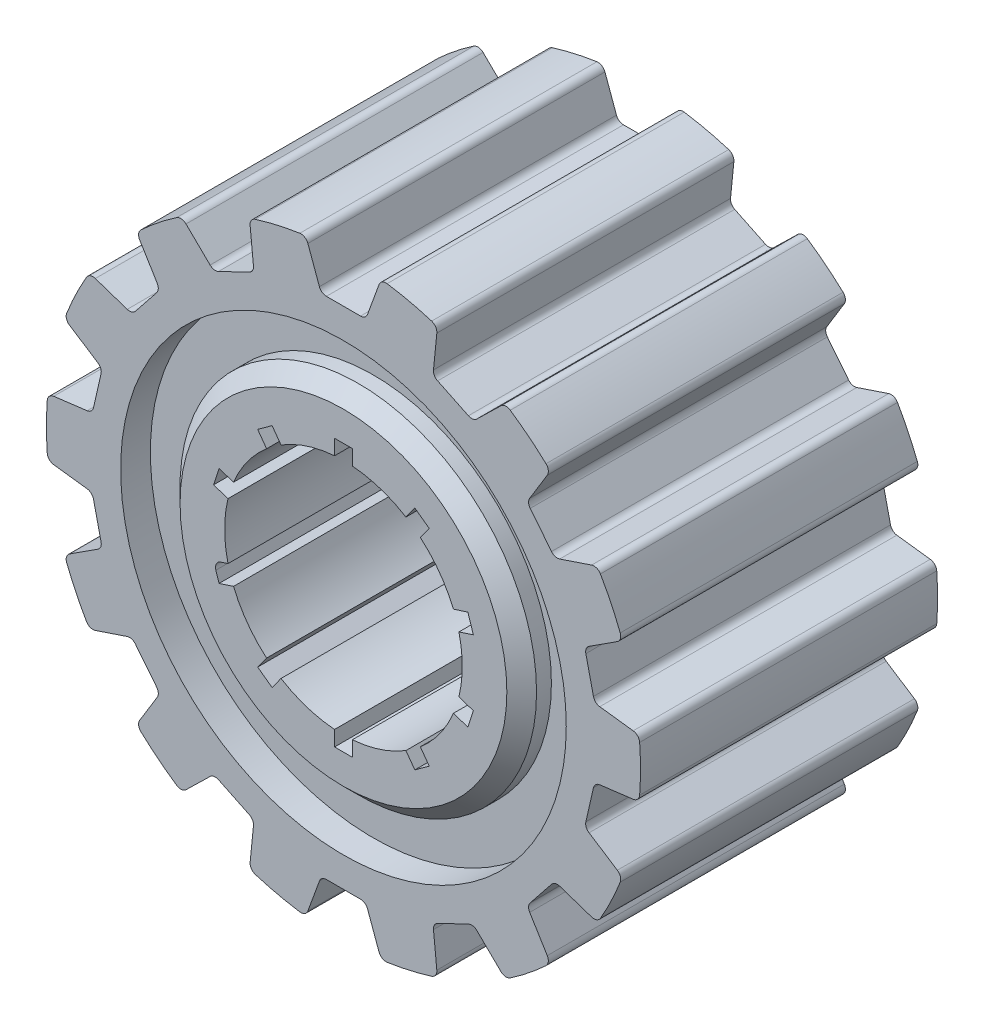
SolidWorks part; units mm, degrees
ref_plane "Front Plane" through (0, 0, 0) normal (0, 0, 1) x (1, 0, 0)
ref_plane "Top Plane" through (0, 0, 0) normal (0, 1, 0) x (1, 0, 0)
ref_plane "Right Plane" through (0, 0, 0) normal (1, 0, 0) x (0, 0, -1)
sketch "Sketch1" plane through (0, 0, 0) normal (0, 0, 1) x (1, 0, 0)
  line L0 (0, 0) -> (0, 1.4505) construction
  line L1 (0, 2.9752) -> (0, 4) construction
  line L2 (-0.3, 1.4505) -> (0.3, 1.4505)
  line L3 (-0.3, 3.9887) -> (-0.3, 4.5)
  line L4 (-0.3, 4.5) -> (0.3, 4.5)
  line L5 (0.3, 3.9887) -> (0.3, 4.5)
  line L6 (2.1018, 3.4033) -> (2.4023, 3.8169)
  line L7 (2.4023, 3.8169) -> (2.8877, 3.4642)
  line L8 (0, 4.5) -> (0, 6.1067) construction
  line L9 (2.5872, 3.0506) -> (2.8877, 3.4642)
  line L10 (3.7008, 1.5179) -> (4.187, 1.6759)
  line L11 (4.187, 1.6759) -> (4.3725, 1.1053)
  line L12 (3.8862, 0.9473) -> (4.3725, 1.1053)
  line L13 (3.8862, -0.9473) -> (4.3725, -1.1053)
  line L14 (4.3725, -1.1053) -> (4.187, -1.6759)
  line L15 (3.7008, -1.5179) -> (4.187, -1.6759)
  line L16 (2.5872, -3.0506) -> (2.8877, -3.4642)
  line L17 (2.8877, -3.4642) -> (2.4023, -3.8169)
  line L18 (2.1018, -3.4033) -> (2.4023, -3.8169)
  line L19 (0.3, -3.9887) -> (0.3, -4.5)
  line L20 (0.3, -4.5) -> (-0.3, -4.5)
  line L21 (-0.3, -3.9887) -> (-0.3, -4.5)
  line L22 (-2.1018, -3.4033) -> (-2.4023, -3.8169)
  line L23 (-2.4023, -3.8169) -> (-2.8877, -3.4642)
  line L24 (-2.5872, -3.0506) -> (-2.8877, -3.4642)
  line L25 (-3.7008, -1.5179) -> (-4.187, -1.6759)
  line L26 (-4.187, -1.6759) -> (-4.3725, -1.1053)
  line L27 (-3.8862, -0.9473) -> (-4.3725, -1.1053)
  line L28 (-3.8862, 0.9473) -> (-4.3725, 1.1053)
  line L29 (-4.3725, 1.1053) -> (-4.187, 1.6759)
  line L30 (-3.7008, 1.5179) -> (-4.187, 1.6759)
  line L31 (-2.5872, 3.0506) -> (-2.8877, 3.4642)
  line L32 (-2.8877, 3.4642) -> (-2.4023, 3.8169)
  line L33 (-2.1018, 3.4033) -> (-2.4023, 3.8169)
  circle A0 centre (0, 0) radius 10
  arc A1 (-0.3, 3.9887) -> (-2.1018, 3.4033) centre (0, 0) ccw
  arc A2 (2.1018, 3.4033) -> (0.3, 3.9887) centre (0, 0) ccw
  arc A3 (-2.5872, 3.0506) -> (-3.7008, 1.5179) centre (0, 0) ccw
  arc A4 (-3.8862, 0.9473) -> (-3.8862, -0.9473) centre (0, 0) ccw
  arc A5 (3.7008, 1.5179) -> (2.5872, 3.0506) centre (0, 0) ccw
  arc A6 (3.8862, -0.9473) -> (3.8862, 0.9473) centre (0, 0) ccw
  arc A7 (2.5872, -3.0506) -> (3.7008, -1.5179) centre (0, 0) ccw
  arc A8 (0.3, -3.9887) -> (2.1018, -3.4033) centre (0, 0) ccw
  arc A9 (-2.1018, -3.4033) -> (-0.3, -3.9887) centre (0, 0) ccw
  arc A10 (-3.7008, -1.5179) -> (-2.5872, -3.0506) centre (0, 0) ccw
  point P4 (0, 2.9752)
  point P10 (0, 4.5)
  point P55 (0, 0)
  dimension "D1" = 20
  dimension "D2" = 8
  dimension "D3" = 0.6
  dimension "D4" = 4.5
  dimension "D5" = 10
extrude "Boss-Extrude1" add sketch "Sketch1" along normal blind 10 contours A0 A10 L25 L26 L27 A4 L28 L29 L30 A3 L31 L32 L33 A1 L3 L4 L5 A2 L6 L7 L9 A5 L10 L11 L12 A6 L13 L14 L15 A7 L16 L17 L18 A8 L19 L20 L21 A9 L22 L23 L24
sketch "Sketch2" plane through (0, 0, 10) normal (0, 0, 1) x (1, 0, 0)
  line L0 (0, 0) -> (0, 10) construction
  line L1 (0.75, 8.5) -> (1.2666, 9.9195)
  line L2 (0.75, 8.5) -> (-0.75, 8.5)
  line L3 (-0.75, 8.5) -> (-1.2666, 9.9195)
  circle A0 centre (0, 0) radius 10 construction
  circle A1 centre (0, 0) radius 10
  circle M47 centre (0, 0) radius 10
  dimension "D1" = 1.5
  dimension "D2" = 20
  dimension "D3" = 8.5
  dimension "D4" = 20
extrude "Cut-Extrude1" cut sketch "Sketch2" against normal through all contours L2 L0 A1 L3 | L0 L2 L1 M47
pattern_circular "CirPattern1" count 14 over 360 about axis through (0, 0, 0) along (0, 0, 1) of "Cut-Extrude1"
ref_plane "Plane1" through (0, 0, 5) normal (0, 0, 1) x (1, 0, 0)
sketch "Sketch3" plane through (0, 0, 5) normal (0, 0, 1) x (1, 0, 0)
  circle A0 centre (0, 0) radius 7.5
  circle A1 centre (0, 0) radius 6
  dimension "D1" = 15
  dimension "D2" = 12
extrude "Cut-Extrude2" cut sketch "Sketch3" against normal through all from offset 4 offset against normal yes
chamfer "Chamfer1" distance 0.5 angle 45 1 edges at (6, 0, 0)
mirror "Mirror2" about plane through (0, 0, 5) normal (0, 0, 1) of "Cut-Extrude2"
chamfer "Chamfer2" distance 0.5 angle 45 1 edges at (6, 0, 10)
fillet "Fillet1" radius 0.25 57 edges at (-1.2666, 9.9195, 5) (-0.75, 8.5, 5) (-7.1132, 4.7133, 5) (-3.0123, -7.9836, 5) (0.75, -8.5, 5) (8.4538, 1.1602, 5) (7.1132, 4.7133, 5) (8.5451, 5.1944, 5) (6.9656, 7.175, 5) (6.178, 5.886, 5) (3.0123, 7.9836, 5) (4.3637, 7.3328, 5) (5.4451, 8.3875, 5) (3.1627, 9.4867, 5) (8.12, -2.6226, 5) (6.9656, -7.175, 5) (8.12, 2.6226, 5) (9.3889, 3.4422, 5) (9.9526, 0.9724, 5) (9.9526, -0.9724, 5) (8.4538, -1.1602, 5) (9.3889, -3.4422, 5) (8.5451, -5.1944, 5) (6.178, -5.886, 5) (7.1132, -4.7133, 5) (4.3637, -7.3328, 5) (5.4451, -8.3875, 5) (3.0123, -7.9836, 5) (3.1627, -9.4867, 5) (1.2666, -9.9195, 5) (-4.3725, -1.1053, 5) (-0.75, -8.5, 5) (-4.3637, -7.3328, 5) (-1.2666, -9.9195, 5) (-3.1627, -9.4867, 5) (-5.4451, -8.3875, 5) (-6.178, -5.886, 5) (-6.9656, -7.175, 5) (-8.5451, -5.1944, 5) (-7.1132, -4.7133, 5) (-8.4538, -1.1602, 5) (-8.12, 2.6226, 5) (-8.4538, 1.1602, 5) (-8.12, -2.6226, 5) (-9.3889, -3.4422, 5) (-9.9526, -0.9724, 5) (-9.3889, 3.4422, 5) (-9.9526, 0.9724, 5) (-8.5451, 5.1944, 5) (-6.9656, 7.175, 5) (-6.178, 5.886, 5) (-5.4451, 8.3875, 5) (-4.3637, 7.3328, 5) (-3.0123, 7.9836, 5) (-3.1627, 9.4867, 5) (1.2666, 9.9195, 5) (0.75, 8.5, 5)
